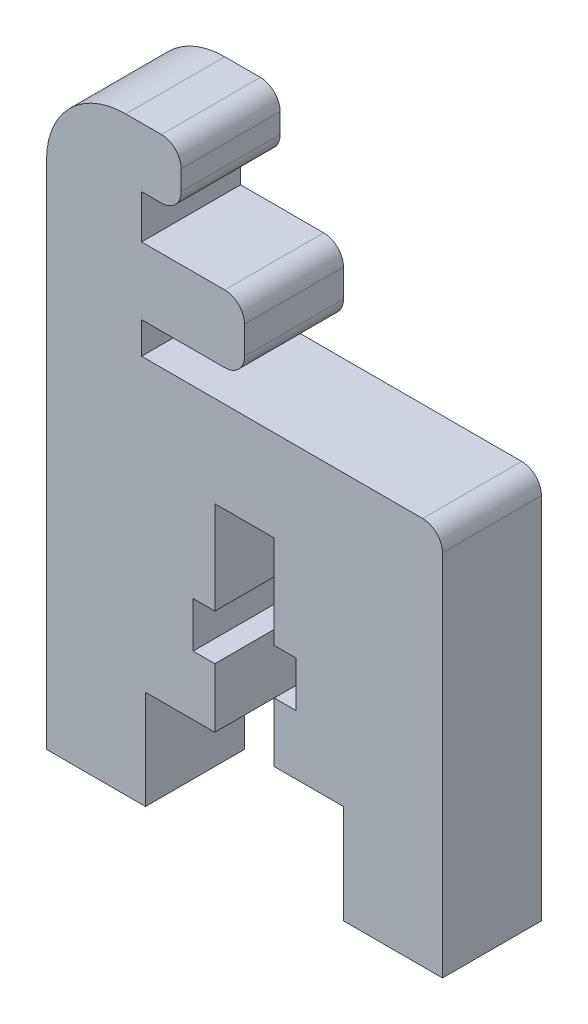
SolidWorks part; units mm, degrees
ref_plane "Front Plane" through (0, 0, 0) normal (0, 0, 1) x (1, 0, 0)
ref_plane "Top Plane" through (0, 0, 0) normal (0, 1, 0) x (1, 0, 0)
ref_plane "Right Plane" through (0, 0, 0) normal (1, 0, 0) x (0, 0, -1)
sketch "Sketch1" plane through (0, 0, 0) normal (0, 0, 1) x (1, 0, 0)
  line L0 (0, 5) -> (0, 19.9828)
  line L1 (20, 5) -> (20, 19.6)
  line L2 (20, 19.6) -> (4.8, 19.6)
  line L3 (4.8, 19.6) -> (4.8, 21.2)
  line L4 (4.8, 21.2) -> (10, 21.2)
  line L5 (10, 21.2) -> (10, 24.6)
  line L7 (0, 24.6) -> (0, 19.9828)
  line L8 (10, 5) -> (10, 16.2208) construction
  line L9 (8.5, 5) -> (5, 5)
  line L10 (5, 0) -> (0, 0)
  line L11 (0, 0) -> (0, 5)
  line L12 (5, 0) -> (5, 5)
  line L13 (11.5, 5) -> (15, 5)
  line L14 (15, 5) -> (15, 0)
  line L15 (15, 0) -> (20, 0)
  line L16 (20, 0) -> (20, 5)
  line L17 (8.5, 5) -> (11.5, 5) construction
  line L18 (11.5, 5) -> (11.5, 8)
  line L19 (11.5, 10.3) -> (12.6, 10.3)
  line L20 (7.4, 8) -> (7.4, 10.3)
  line L21 (12.6, 8) -> (11.5, 8)
  line L22 (11.5, 10.3) -> (11.5, 15)
  line L23 (11.5, 15) -> (8.5, 15)
  line L24 (8.5, 15) -> (8.5, 10.3)
  line L25 (8.5, 8) -> (7.4, 8)
  line L26 (12.6, 10.3) -> (12.6, 8)
  line L27 (7.4, 10.3) -> (8.5, 10.3)
  line L28 (8.5, 8) -> (8.5, 5)
  line L29 (10, 15) -> (10, 5) construction
  line L30 (10, 24.6) -> (4.8, 24.6)
  line L31 (4.8, 24.6) -> (4.8, 26.8)
  line L32 (4.8, 26.8) -> (6.8, 26.8)
  line L33 (6.8, 26.8) -> (6.8, 29.8)
  line L34 (6.8, 29.8) -> (0, 29.8)
  line L35 (0, 29.8) -> (0, 24.6)
  dimension "D1" = 1.6
  dimension "D2" = 14.6
  dimension "D3" = 4.8
  dimension "D4" = 2.2
  dimension "D5" = 10
  dimension "D6" = 5
  dimension "D7" = 5
  dimension "D8" = 5.2
  dimension "D9" = 3
  dimension "D10" = 2.3
  dimension "D11" = 3
  dimension "D12" = 10
  dimension "D13" = 10
  dimension "D14" = 3
  dimension "D15" = 2
extrude "Boss-Extrude1" add sketch "Sketch1" along normal blind 5
fillet "Fillet3" radius 1 2 edges at (20, 19.6, 2.5) (10, 21.2, 2.5)
fillet "Fillet4" radius 1 3 edges at (6.8, 29.8, 2.5) (6.8, 26.8, 2.5) (10, 24.6, 2.5)
fillet "Fillet5" radius 4 1 edges at (0, 29.8, 2.5)
